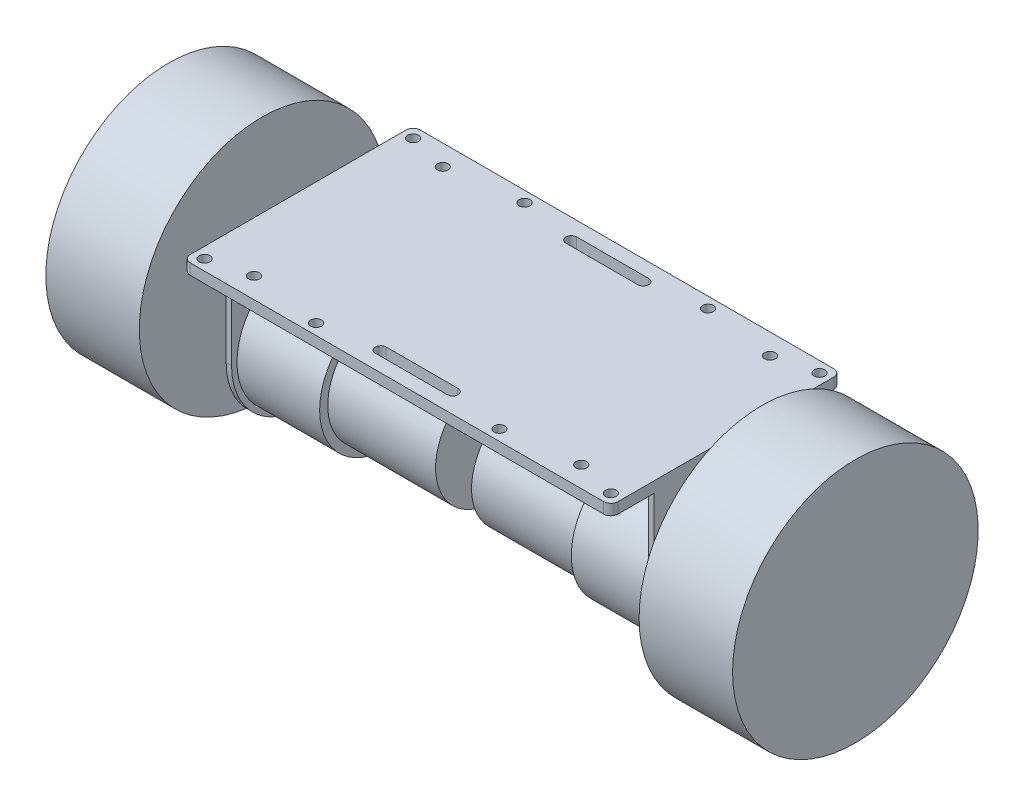
SolidWorks part; units mm, degrees
ref_plane "Front" through (0, 0, 0) normal (0, 0, 1) x (1, 0, 0)
ref_plane "Top" through (0, 0, 0) normal (0, 1, 0) x (1, 0, 0)
ref_plane "Right" through (0, 0, 0) normal (1, 0, 0) x (0, 0, -1)
sketch "Sketch2" plane through (0, 0, 0) normal (0, 1, 0) x (1, 0, 0)
  line L0 (0, 32) -> (0, -32) construction
  line L1 (57.5, -32) -> (-57.5, -32)
  line L2 (59.5, -30) -> (59.5, 30)
  line L3 (57.5, 32) -> (-57.5, 32)
  line L4 (-59.5, -30) -> (-59.5, 30)
  line L5 (59.5, -32) -> (-59.5, 32) construction
  line L6 (59.5, 32) -> (-59.5, -32) construction
  line L7 (59.5, 0) -> (-59.5, 0) construction
  line L8 (10, 28) -> (-10, 28)
  line L9 (-10, 25) -> (10, 25)
  line L10 (-10, -25) -> (10, -25)
  line L11 (10, -28) -> (-10, -28)
  arc A0 (57.5, -32) -> (59.5, -30) centre (57.5, -30) ccw
  arc A1 (59.5, 30) -> (57.5, 32) centre (57.5, 30) ccw
  arc A2 (-57.5, -32) -> (-59.5, -30) centre (-57.5, -30) cw
  arc A3 (-57.5, 32) -> (-59.5, 30) centre (-57.5, 30) ccw
  circle A4 centre (-56.5, 29) radius 1.5
  circle A5 centre (-45.5, 26.25) radius 1.5
  circle A6 centre (-25.5, 29) radius 1.5
  circle A7 centre (-25.5, -29) radius 1.5
  circle A8 centre (-45.5, -26.25) radius 1.5
  circle A9 centre (-56.5, -29) radius 1.5
  circle A10 centre (25.5, -29) radius 1.5
  circle A11 centre (45.5, -26.25) radius 1.5
  circle A12 centre (56.5, -29) radius 1.5
  circle A13 centre (56.5, 29) radius 1.5
  circle A14 centre (45.5, 26.25) radius 1.5
  circle A15 centre (25.5, 29) radius 1.5
  arc A16 (-10, 28) -> (-10, 25) centre (-10, 26.5) ccw
  arc A17 (10, 28) -> (10, 25) centre (10, 26.5) cw
  arc A18 (10, -28) -> (10, -25) centre (10, -26.5) ccw
  arc A19 (-10, -28) -> (-10, -25) centre (-10, -26.5) cw
  point P0 (0, 0)
  point P46 (0, 25)
  point P54 (0, 28)
  dimension "D3" = 2
  dimension "D4" = 3
  dimension "D7" = 3
  dimension "D10" = 4
  dimension "D13" = 10
  dimension "D1" = 64
  dimension "D2" = 119
  dimension "D5" = 3
  dimension "D6" = 3
  dimension "D8" = 5.75
  dimension "D9" = 3
  dimension "D11" = 34
  dimension "D12" = 14
extrude "Boss-Extrude1" add sketch "Sketch2" along normal blind 3
sketch "Sketch4" plane through (0, 0, 0) normal (0, -1, 0) x (1, 0, 0)
  line L0 (-59.5, 0) -> (59.5, 0) construction
  line L1 (-59.5, -30) -> (-59.5, 30) construction
  line L2 (59.5, 30) -> (59.5, -30) construction
  line L4 (-58, -20) -> (-59.5, -20)
  line L5 (-58, -20) -> (-58, 20)
  line L6 (-58, 20) -> (-59.5, 20)
  line L7 (-59.5, -20) -> (-59.5, 20)
  line L8 (-58, -20) -> (-59.5, 20) construction
  line L9 (-58, 20) -> (-59.5, -20) construction
  point P6 (-58.75, 0)
  dimension "D1" = 1.5
  dimension "D2" = 40
extrude "Boss-Extrude2" add sketch "Sketch4" along normal blind 48
mirror "Mirror3" about plane through (0, 0, 0) normal (1, 0, 0) of "Boss-Extrude2"
sketch "Sketch5" plane through (-59.5, 0, 0) normal (-1, 0, 0) x (0, 0, 1)
  line L0 (-20, -48) -> (-20, 0) construction
  line L1 (20, -48) -> (20, 0) construction
  line L2 (-20, -28) -> (20, -28) construction
  line L3 (20, -48) -> (-20, -48) construction
  line L4 (-20, -28) -> (-20, -48)
  line L5 (-20, -48) -> (20, -48)
  line L6 (20, -48) -> (20, -28)
  arc A0 (-20, -28) -> (20, -28) centre (0, -28) ccw
  line M4 (-20, 0) -> (-20, -48)
  line M5 (-20, -48) -> (20, -48)
  line M6 (20, -48) -> (20, 0)
extrude "Cut-Extrude1" cut sketch "Sketch5" against normal through all contours A0 M4 M5 | A0 L5 M6
sketch "Sketch6" plane through (-58, 0, 0) normal (1, 0, 0) x (0, 0, -1)
  line L0 (-20, -28) -> (20, -28) construction
  circle A0 centre (0, -28) radius 18.5
  arc A1 (-20, -28) -> (20, -28) centre (0, -28) ccw construction
  dimension "D1" = 1.5
extrude "Boss-Extrude3" add sketch "Sketch6" along normal blind 23
sketch "Sketch7" plane through (-35, 0, 0) normal (1, 0, 0) x (0, 0, -1)
  circle A0 centre (0, -28) radius 16.25
extrude "Boss-Extrude4" add sketch "Sketch7" along normal blind 30
sketch "Sketch8" plane through (-59.5, 0, 0) normal (-1, 0, 0) x (0, 0, 1)
  line L0 (0, 3) -> (0, -48) construction
  line L1 (-30, 3) -> (30, 3) construction
  line L2 (-20, -18) -> (20, -18) construction
  line L3 (-20, -28) -> (-20, 0) construction
  line L4 (20, -28) -> (20, 0) construction
  arc A0 (-20, -28) -> (20, -28) centre (0, -28) ccw construction
  circle A1 centre (0, -18) radius 6
  point P13 (0, -18)
  dimension "D2" = 12
  dimension "D1" = 21
extrude "Boss-Extrude5" add sketch "Sketch8" along normal blind 10
sketch "Sketch9" plane through (-69.5, 0, 0) normal (-1, 0, 0) x (0, 0, 1)
  circle A0 centre (0, -18) radius 34.15
  dimension "D1" = 68.3
extrude "Boss-Extrude6" add sketch "Sketch9" along normal blind 26
mirror "Mirror7" about plane through (0, 0, 0) normal (1, 0, 0) of "Boss-Extrude5", "Boss-Extrude6", "Boss-Extrude4", "Boss-Extrude3"
